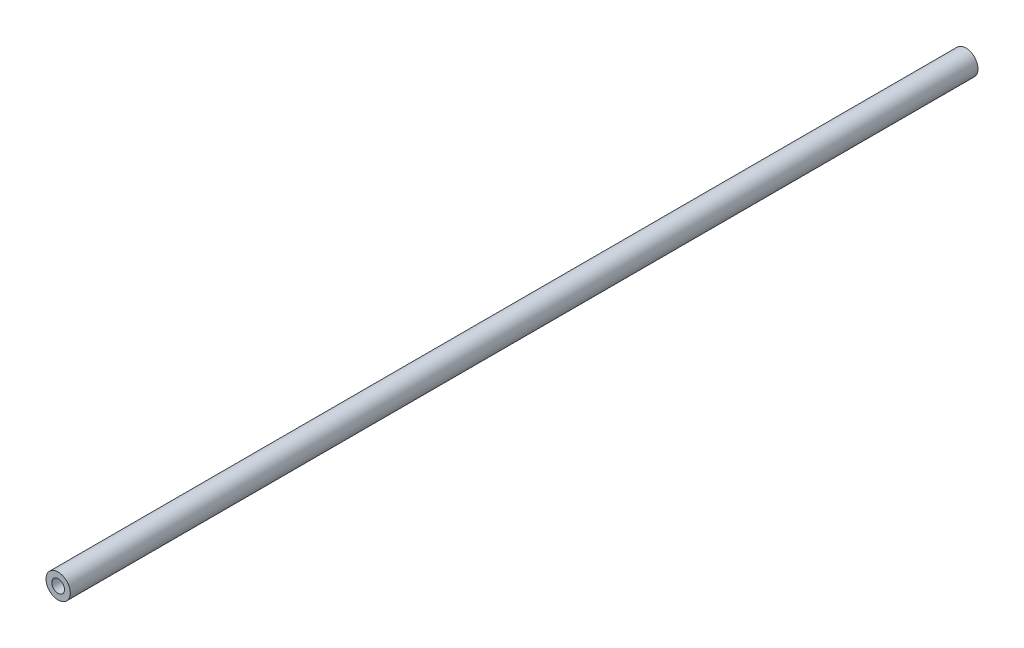
SolidWorks part; units mm, degrees
material "6061-T6 (SS)"
ref_plane "Front Plane" through (0, 0, 0) normal (0, 0, 1) x (1, 0, 0)
ref_plane "Top Plane" through (0, 0, 0) normal (0, 1, 0) x (1, 0, 0)
ref_plane "Right Plane" through (0, 0, 0) normal (1, 0, 0) x (0, 0, -1)
sketch "Sketch1" plane through (0, 0, 0) normal (0, 0, 1) x (1, 0, 0)
  circle A0 centre (0, 0) radius 4.7625
  circle A1 centre (0, 0) radius 2.4892
  dimension "D1" = 9.525
  dimension "D2" = 4.9784
extrude "Boss-Extrude1" add sketch "Sketch1" along normal mid plane 355.6
